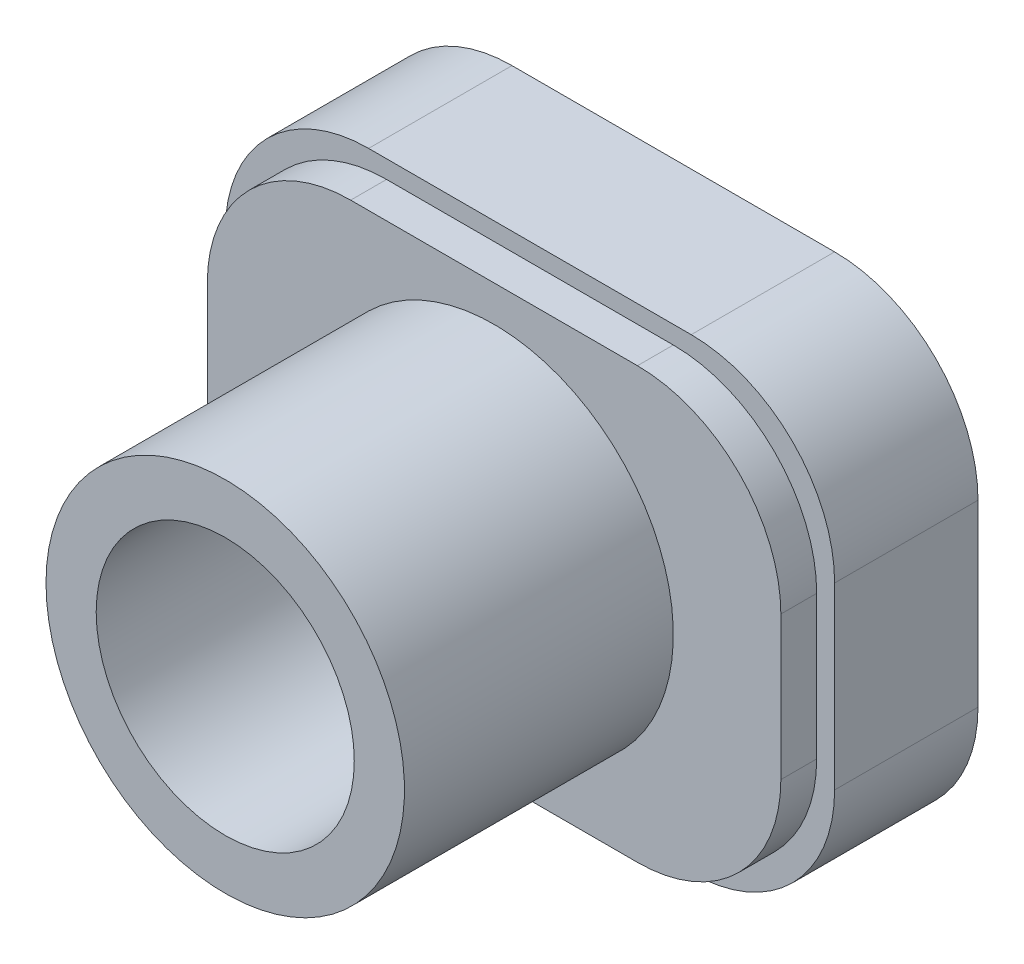
SolidWorks part; units mm, degrees
ref_plane "Front Plane" through (0, 0, 0) normal (0, 0, 1) x (1, 0, 0)
ref_plane "Top Plane" through (0, 0, 0) normal (0, 1, 0) x (1, 0, 0)
ref_plane "Right Plane" through (0, 0, 0) normal (1, 0, 0) x (0, 0, -1)
sketch "Sketch1" plane through (0, 0, 0) normal (0, 0, 1) x (1, 0, 0)
  line L1 (3.67, -6) -> (-3.67, -6)
  line L2 (8.75, -0.92) -> (8.75, 0.92)
  line L3 (3.67, 6) -> (-3.67, 6)
  line L4 (-8.75, -0.92) -> (-8.75, 0.92)
  line L5 (8.75, -6) -> (-8.75, 6) construction
  line L6 (8.75, 6) -> (-8.75, -6) construction
  line L7 (5.715, -8.255) -> (-5.715, -8.255)
  line L8 (10.795, -3.175) -> (10.795, 3.175)
  line L9 (5.715, 8.255) -> (-5.715, 8.255)
  line L10 (-10.795, -3.175) -> (-10.795, 3.175)
  line L11 (10.795, -8.255) -> (-10.795, 8.255) construction
  line L12 (10.795, 8.255) -> (-10.795, -8.255) construction
  arc A0 (3.67, 6) -> (8.75, 0.92) centre (3.67, 0.92) cw
  arc A1 (8.75, -0.92) -> (3.67, -6) centre (3.67, -0.92) cw
  arc A2 (-3.67, -6) -> (-8.75, -0.92) centre (-3.67, -0.92) cw
  arc A3 (-8.75, 0.92) -> (-3.67, 6) centre (-3.67, 0.92) cw
  arc A4 (-10.795, -3.175) -> (-5.715, -8.255) centre (-5.715, -3.175) ccw
  arc A5 (5.715, -8.255) -> (10.795, -3.175) centre (5.715, -3.175) ccw
  arc A6 (10.795, 3.175) -> (5.715, 8.255) centre (5.715, 3.175) ccw
  arc A7 (-10.795, 3.175) -> (-5.715, 8.255) centre (-5.715, 3.175) cw
  point P0 (0, 0)
  point P18 (0, 0)
  dimension "D3" = 5.08
  dimension "D6" = 5.08
  dimension "D1" = 12
  dimension "D2" = 17.5
  dimension "D4" = 16.51
  dimension "D5" = 21.59
extrude "Boss-Extrude1" add sketch "Sketch1" along normal blind 5.08
sketch "Sketch2" plane through (0, 0, 5.08) normal (0, 0, 1) x (1, 0, 0)
  line L1 (5.08, -7.62) -> (-5.08, -7.62)
  line L2 (10.16, -2.54) -> (10.16, 2.54)
  line L3 (5.08, 7.62) -> (-5.08, 7.62)
  line L4 (-10.16, -2.54) -> (-10.16, 2.54)
  line L5 (10.16, -7.62) -> (-10.16, 7.62) construction
  line L6 (10.16, 7.62) -> (-10.16, -7.62) construction
  arc A0 (-10.16, -2.54) -> (-5.08, -7.62) centre (-5.08, -2.54) ccw
  arc A1 (5.08, -7.62) -> (10.16, -2.54) centre (5.08, -2.54) ccw
  arc A2 (10.16, 2.54) -> (5.08, 7.62) centre (5.08, 2.54) ccw
  arc A3 (-10.16, 2.54) -> (-5.08, 7.62) centre (-5.08, 2.54) cw
  point P0 (0, 0)
  dimension "D3" = 5.08
  dimension "D1" = 15.24
  dimension "D2" = 20.32
extrude "Boss-Extrude2" add sketch "Sketch2" along normal blind 1.27
sketch "Sketch4" plane through (0, 0, 6.35) normal (0, 0, 1) x (1, 0, 0)
  circle A0 centre (0, 0) radius 6.35
  dimension "D1" = 12.7
extrude "Boss-Extrude3" add sketch "Sketch4" along normal blind 9.525
sketch "Sketch5" plane through (0, 0, 15.875) normal (0, 0, 1) x (1, 0, 0)
  circle A0 centre (0, 0) radius 4.572
  dimension "D1" = 9.144
extrude "Cut-Extrude1" cut sketch "Sketch5" against normal blind 12.7
